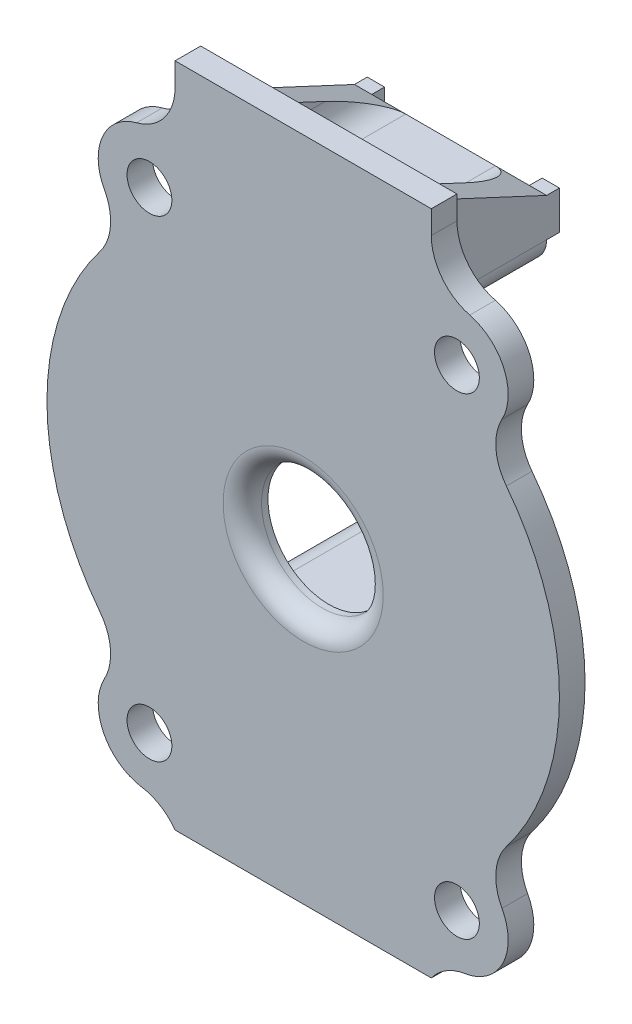
SolidWorks part; units mm, degrees
material "PP Copolymer"
ref_plane "Alzado" through (0, 0, 0) normal (0, 0, 1) x (1, 0, 0)
ref_plane "Planta" through (0, 0, 0) normal (0, 1, 0) x (1, 0, 0)
ref_plane "Vista lateral" through (0, 0, 0) normal (1, 0, 0) x (0, 0, -1)
sketch "Croquis1" plane through (0, 0, 0) normal (0, 0, 1) x (1, 0, 0)
  line L12 (10, -24) -> (8, -24) construction
  line L13 (-8, -24) -> (-10, -24) construction
  line L14 (-8, -24) -> (8, -24) construction
  line L15 (10, -24) -> (8, -24)
  line L16 (-8, -24) -> (-10, -24)
  line L17 (-8, -24) -> (8, -24)
  line L18 (10, 28) -> (10, 26.1851)
  line L19 (-10, 28) -> (-10, 26.1851)
  line L20 (10, 28) -> (-10, 28)
  arc A56 (12.6214, -22.3905) -> (10, -24) centre (13.2427, -26.342) ccw construction
  arc A57 (12.6214, -22.3905) -> (15.5155, -16.5309) centre (12, -18.4391) ccw construction
  arc A58 (15.8592, -12.1855) -> (15.5155, -16.5309) centre (19.031, -14.6226) ccw construction
  arc A59 (15.5155, 16.5309) -> (15.8592, 12.1855) centre (19.031, 14.6226) ccw construction
  arc A60 (15.8592, -12.1855) -> (15.8592, 12.1855) centre (0, 0) ccw construction
  arc A61 (15.5155, 16.5309) -> (13.0807, 22.2903) centre (12, 18.4391) ccw construction
  arc A68 (-13.0807, 22.2903) -> (-15.5155, 16.5309) centre (-12, 18.4391) ccw construction
  arc A69 (-15.8592, 12.1855) -> (-15.5155, 16.5309) centre (-19.031, 14.6226) ccw construction
  arc A70 (-15.8592, 12.1855) -> (-15.8592, -12.1855) centre (0, 0) ccw construction
  arc A71 (-15.5155, -16.5309) -> (-15.8592, -12.1855) centre (-19.031, -14.6226) ccw construction
  arc A72 (-15.5155, -16.5309) -> (-12.6214, -22.3905) centre (-12, -18.4391) ccw construction
  arc A73 (-10, -24) -> (-12.6214, -22.3905) centre (-13.2427, -26.342) ccw construction
  arc A74 (12.6214, -22.3905) -> (10, -24) centre (13.2427, -26.342) ccw
  arc A75 (12.6214, -22.3905) -> (15.5155, -16.5309) centre (12, -18.4391) ccw
  arc A76 (15.8592, -12.1855) -> (15.5155, -16.5309) centre (19.031, -14.6226) ccw
  arc A77 (15.5155, 16.5309) -> (15.8592, 12.1855) centre (19.031, 14.6226) ccw
  arc A78 (15.8592, -12.1855) -> (15.8592, 12.1855) centre (0, 0) ccw
  arc A79 (15.5155, 16.5309) -> (13, 22.3121) centre (12, 18.4391) ccw
  arc A80 (-13, 22.3121) -> (-10, 26.1851) centre (-14, 26.1851) ccw
  circle A81 centre (-12, -18.4391) radius 1.75
  circle A82 centre (12, -18.4391) radius 1.75
  circle A83 centre (12, 18.4391) radius 1.75
  circle A84 centre (-12, 18.4391) radius 1.75
  arc A85 (13, 22.3121) -> (10, 26.1851) centre (14, 26.1851) cw
  arc A86 (-13, 22.3121) -> (-15.5155, 16.5309) centre (-12, 18.4391) ccw
  arc A87 (-15.8592, 12.1855) -> (-15.5155, 16.5309) centre (-19.031, 14.6226) ccw
  arc A88 (-15.8592, 12.1855) -> (-15.8592, -12.1855) centre (0, 0) ccw
  arc A89 (-15.5155, -16.5309) -> (-15.8592, -12.1855) centre (-19.031, -14.6226) ccw
  arc A90 (-15.5155, -16.5309) -> (-12.6214, -22.3905) centre (-12, -18.4391) ccw
  arc A91 (-10, -24) -> (-12.6214, -22.3905) centre (-13.2427, -26.342) ccw
  circle A92 centre (0, 0) radius 4.75
  dimension "D1" = 9.5
  dimension "D2" = 3.5
  dimension "D3" = 4
extrude "Saliente-Extruir1" add sketch "Croquis1" along normal blind 2
fillet "Redondeo1" radius 1.5 1 edges at (4.75, 0, 2)
sketch "Croquis2" plane through (0, 0, 0) normal (1, 0, 0) x (0, 0, -1)
  line L1 (9.5, 21.9) -> (0, 21.9)
  line L2 (9.5, 21.9) -> (9.5, 16.9)
  line L3 (9.5, 16.9) -> (0, 16.9)
  line L4 (0, 21.9) -> (0, 16.9)
  line L5 (9.5, 21.9) -> (0, 16.9) construction
  line L6 (9.5, 16.9) -> (0, 21.9) construction
  line L7 (9.5, -6.6) -> (0, -6.6)
  line L8 (9.5, -6.6) -> (9.5, -11.6)
  line L9 (9.5, -11.6) -> (0, -11.6)
  line L10 (0, -6.6) -> (0, -11.6)
  line L11 (9.5, -6.6) -> (0, -11.6) construction
  line L12 (9.5, -11.6) -> (0, -6.6) construction
  line L13 (9.5, 5.15) -> (0, 5.15) construction
  line L14 (9.5, 16.4) -> (0, 16.4) construction
  line L15 (9.5, -6.1) -> (0, -6.1) construction
  line L16 (0, 12.1855) -> (0, 16.5309) construction
  line L17 (9.5, 5.15) -> (0, 5.15) construction
  line L18 (0, -12.1855) -> (0, 12.1855) construction
  line L19 (9.5, -6.1) -> (0, -6.1) construction
  line L20 (9.5, 16.4) -> (0, 16.4) construction
  point P0 (4.75, 19.4)
  point P5 (4.75, -9.1)
  dimension "D1" = 0.5
  dimension "D3" = 5
  dimension "D4" = 9.5
  dimension "D5" = 11.25
  dimension "D7" = 6.1
  dimension "D6" = 11.25
extrude "Saliente-Extruir2" add sketch "Croquis2" along normal mid plane 15
sketch "Croquis3" plane through (0, 0, -9.5) normal (0, 0, -1) x (-1, 0, 0)
  circle A0 centre (0, -8.75) radius 0.9
  circle A1 centre (0, 19.05) radius 0.9
  dimension "D1" = 1.8
extrude "Cortar-Extruir1" cut sketch "Croquis3" against normal blind 5
sketch "Croquis4" plane through (-7.5, 0, 0) normal (-1, 0, 0) x (0, 0, 1)
  line L0 (-9.5, -11.6) -> (0, -16.0299)
  line L1 (0, -16.0299) -> (0, -11.6)
  line L2 (0, -11.6) -> (-9.5, -11.6)
  line L4 (-9.5, 21.9) -> (0, 21.9)
  line L5 (-9.5, 16.9) -> (-9.5, 21.9) construction
  line L6 (-9.5, 21.9) -> (0, 21.9) construction
  line L7 (0, 21.9) -> (0, 26.3299)
  line L9 (0, 26.3299) -> (-9.5, 21.9)
  line L10 (0, 28) -> (0, 26.1851) construction
  dimension "D1" = 25
  dimension "D2" = 25
extrude "Saliente-Extruir3" add sketch "Croquis4" against normal blind 2
mirror "Simetría1" about plane through (0, 0, 0) normal (1, 0, 0) of "Saliente-Extruir3"
fillet "Redondeo2" radius 2 4 edges at (-5.5, 21.9, -4.75) (5.5, 21.9, -4.75) (-5.5, -11.6, -4.75) (5.5, -11.6, -4.75)
fillet "Redondeo3" radius 2 4 edges at (-7.5, -6.6, -4.75) (7.5, -6.6, -4.75) (-7.5, 16.9, -4.75) (7.5, 16.9, -4.75)
sketch "Croquis5" plane through (0, 0, -9.5) normal (0, 0, -1) x (-1, 0, 0)
  line L0 (0, -11.6) -> (0, -6.6) construction
  line L1 (-7.5, -11.6) -> (-6.15, -11.6)
  line L2 (-7.5, -11.6) -> (-7.5, -8.6)
  line L3 (-7.5, -8.6) -> (-6.15, -8.6)
  line L4 (-6.15, -11.6) -> (-6.15, -8.6)
  line L5 (7.5, -11.6) -> (6.15, -11.6)
  line L6 (7.5, -11.6) -> (7.5, -8.6)
  line L7 (7.5, -8.6) -> (6.15, -8.6)
  line L8 (6.15, -11.6) -> (6.15, -8.6)
  line L9 (-3.5, -11.6) -> (3.5, -11.6) construction
  line L10 (-5.5, -6.6) -> (5.5, -6.6) construction
  line L11 (7.5, -11.6) -> (7.5, -8.6) construction
  line L12 (0, -6.6) -> (0, 16.9) construction
  line L13 (-5.5, 16.9) -> (5.5, 16.9) construction
  line L14 (-7.5, 5.15) -> (7.5, 5.15) construction
  line L15 (0, 21.9) -> (0, 16.9) construction
  line L16 (6.15, 21.9) -> (6.15, 18.9)
  line L17 (7.5, 18.9) -> (6.15, 18.9)
  line L18 (7.5, 21.9) -> (7.5, 18.9)
  line L19 (7.5, 21.9) -> (6.15, 21.9)
  line L20 (-6.15, 21.9) -> (-6.15, 18.9)
  line L21 (-7.5, 18.9) -> (-6.15, 18.9)
  line L22 (-7.5, 21.9) -> (-7.5, 18.9)
  line L23 (-7.5, 21.9) -> (-6.15, 21.9)
  point P21 (0, 5.15)
  dimension "D1" = 12.3
extrude "Saliente-Extruir4" add sketch "Croquis5" along normal blind 1
